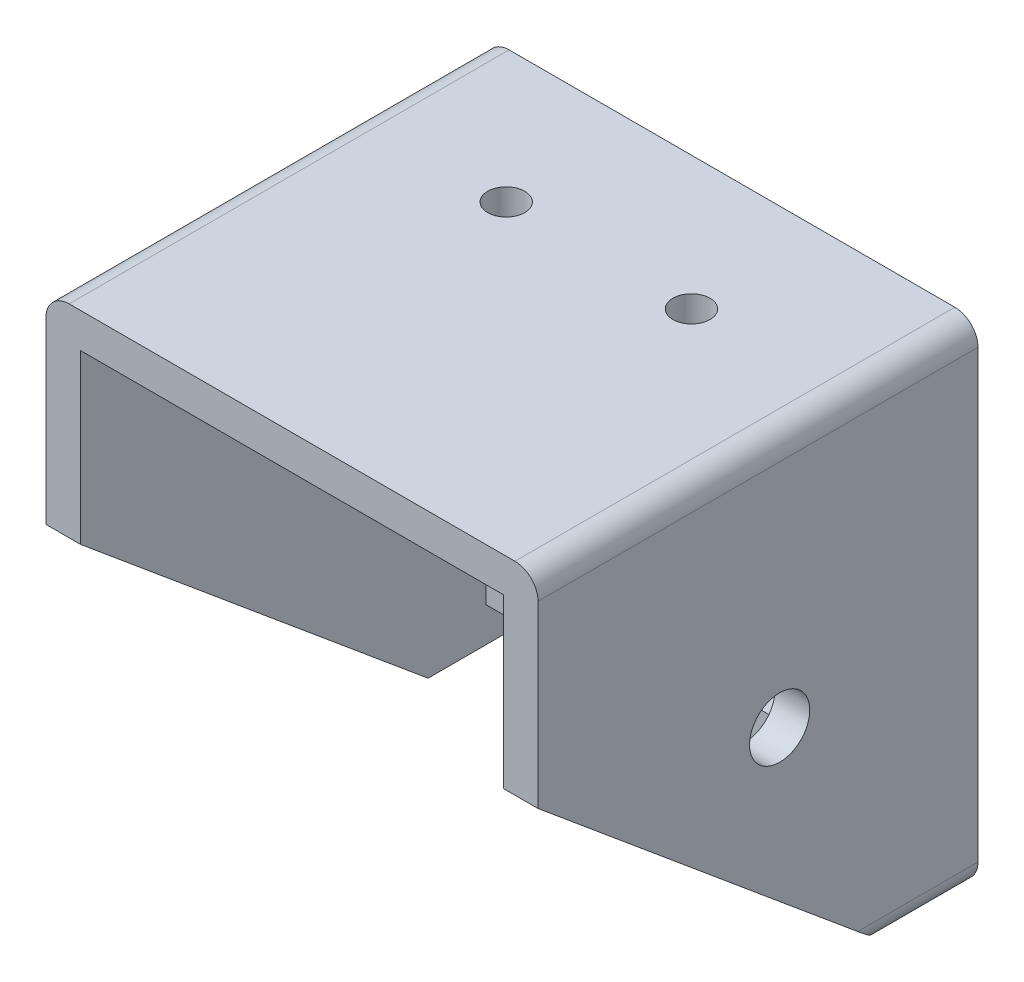
SolidWorks part; units mm, degrees
ref_plane "前视基准面" through (0, 0, 0) normal (0, 0, 1) x (1, 0, 0)
ref_plane "上视基准面" through (0, 0, 0) normal (0, 1, 0) x (1, 0, 0)
ref_plane "右视基准面" through (0, 0, 0) normal (1, 0, 0) x (0, 0, -1)
sketch "草图1" plane through (0, 0, 0) normal (0, 0, 1) x (1, 0, 0)
  line L0 (0, 0) -> (0, 14.5)
  line L1 (0, 0) -> (26.5, 0)
  line L2 (0, 14.5) -> (26.5, 14.5)
  line L3 (26.5, 14.5) -> (26.5, 0)
  line L4 (29.5, -7) -> (34.5, -7)
  line L5 (34.5, -7) -> (34.5, 35.5)
  line L6 (34.5, 35.5) -> (29.5, 35.5)
  line L7 (-3, 35.5) -> (-8, 35.5)
  line L9 (-3, -7) -> (29.5, -7)
  line L10 (-8, 35.5) -> (-8, -7)
  line L11 (29.5, 35.5) -> (-3, 35.5)
  line L12 (-8, -7) -> (-3, -7)
extrude "凸台-拉伸1" add sketch "草图1" along normal blind 3
sketch "草图4" plane through (0, 0, 3) normal (0, 0, 1) x (1, 0, 0)
  circle A0 centre (3.25, 25.5) radius 6
  circle A1 centre (23.25, 25.5) radius 6
extrude "切除-拉伸1" cut sketch "草图4" against normal blind 20
sketch "草图5" plane through (0, 0, 3) normal (0, 0, 1) x (1, 0, 0)
  line L0 (-8, 35.5) -> (-8, 32.5)
  line L1 (-8, -7) -> (34.5, -7)
  line L2 (34.5, -7) -> (34.5, 35.5)
  line L3 (34.5, 35.5) -> (-8, 35.5)
  line L4 (-8, 35.5) -> (-8, -7) construction
  line L5 (-5, 32.5) -> (31.5, 32.5)
  line L6 (31.5, 32.5) -> (31.5, -4)
  line L7 (31.5, -4) -> (-5, -4)
  line L8 (-5, -4) -> (-5, 32.5)
  line L9 (-8, 32.5) -> (-8, -7)
extrude "凸台-拉伸3" add sketch "草图5" along normal blind 35
sketch "草图8" plane through (-8, 0, 0) normal (-1, 0, 0) x (0, 0, 1)
  line L0 (38, -7) -> (38, 8)
  line L1 (38, 35.5) -> (38, -7) construction
  line L2 (38, -7) -> (8, -7)
  line L3 (38, 8) -> (38, 18)
  line L4 (8, -7) -> (38, 18)
  line L5 (38, -7) -> (0, -7) construction
extrude "切除-拉伸3" cut sketch "草图8" against normal blind 45
sketch "草图9" plane through (34.5, 0, 0) normal (1, 0, 0) x (0, 0, -1)
  circle A0 centre (-17.1321, 13.6272) radius 2.6
extrude "切除-拉伸4" cut sketch "草图9" against normal blind 26
fillet "圆角1" radius 2 4 edges at (-8, 35.5, 19) (34.5, 35.5, 19) (-8, -7, 4) (34.5, -7, 4)
sketch "草图10" plane through (0, 35.5, 0) normal (0, 1, 0) x (1, 0, 0)
  circle A0 centre (21.25, -11.5) radius 1.6
  circle A1 centre (5.25, -11.5) radius 1.6
extrude "切除-拉伸5" cut sketch "草图10" against normal blind 9
sketch "草图11" plane through (-5, 0, 0) normal (1, 0, 0) x (0, 0, -1)
  line L1 (-3, -7) -> (0, -7)
  line L2 (0, -7) -> (-3, -4)
  line L3 (-3, -7) -> (-14.238, -7)
  line L4 (-14.238, -7) -> (-14.238, -4)
  line L5 (-14.238, -4) -> (-3, -4)
extrude "切除-拉伸6" cut sketch "草图11" along normal blind 36.5
